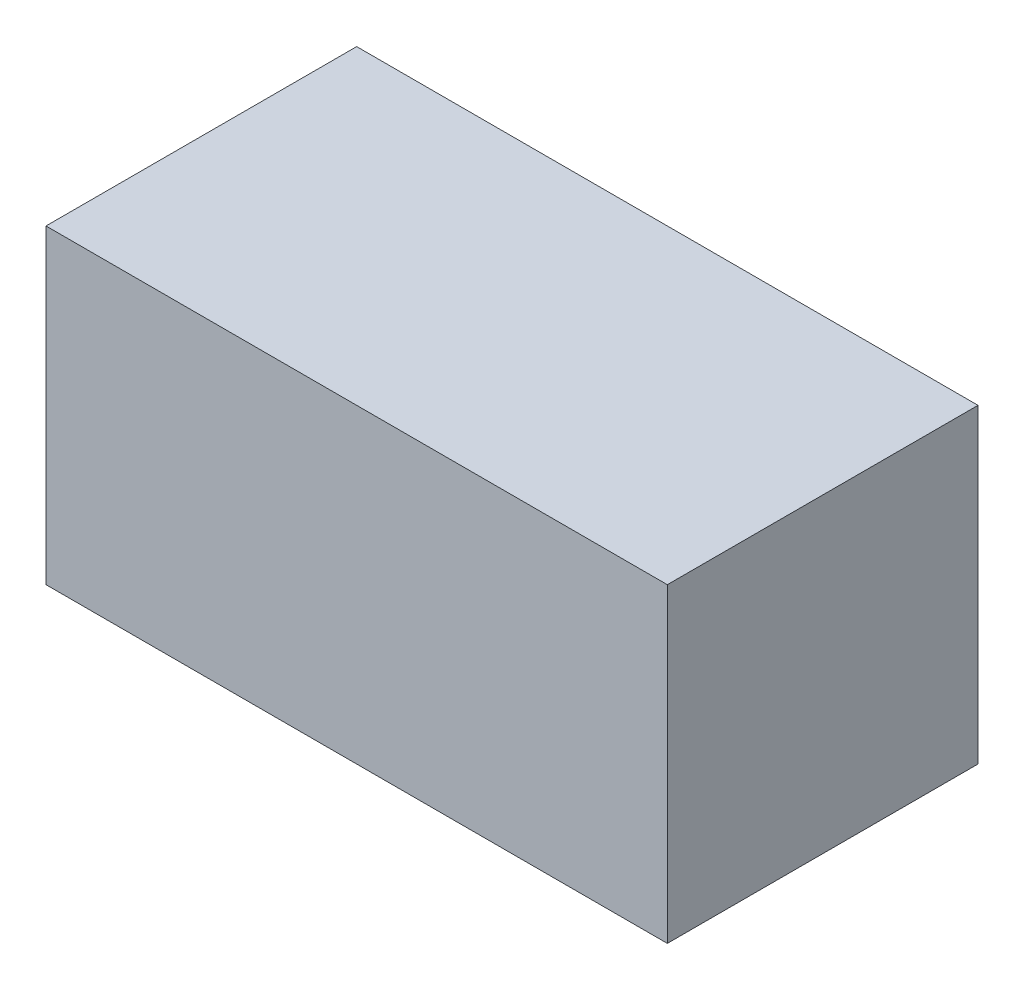
SolidWorks part; units mm, degrees
ref_plane "Front Plane" through (0, 0, 0) normal (0, 0, 1) x (1, 0, 0)
ref_plane "Top Plane" through (0, 0, 0) normal (0, 1, 0) x (1, 0, 0)
ref_plane "Right Plane" through (0, 0, 0) normal (1, 0, 0) x (0, 0, -1)
sketch "Sketch1" plane through (0, 0, 0) normal (0, 1, 0) x (1, 0, 0)
  line L1 (0, 0) -> (20, 0)
  line L2 (0, 0) -> (0, 10)
  line L3 (0, 10) -> (20, 10)
  line L4 (20, 0) -> (20, 10)
  dimension "D1" = 10
  dimension "D2" = 20
extrude "Boss-Extrude1" add sketch "Sketch1" along normal blind 10
ref_plane "Plane1" through (10, 0, 0) normal (1, 0, 0) x (0, 0, -1)
